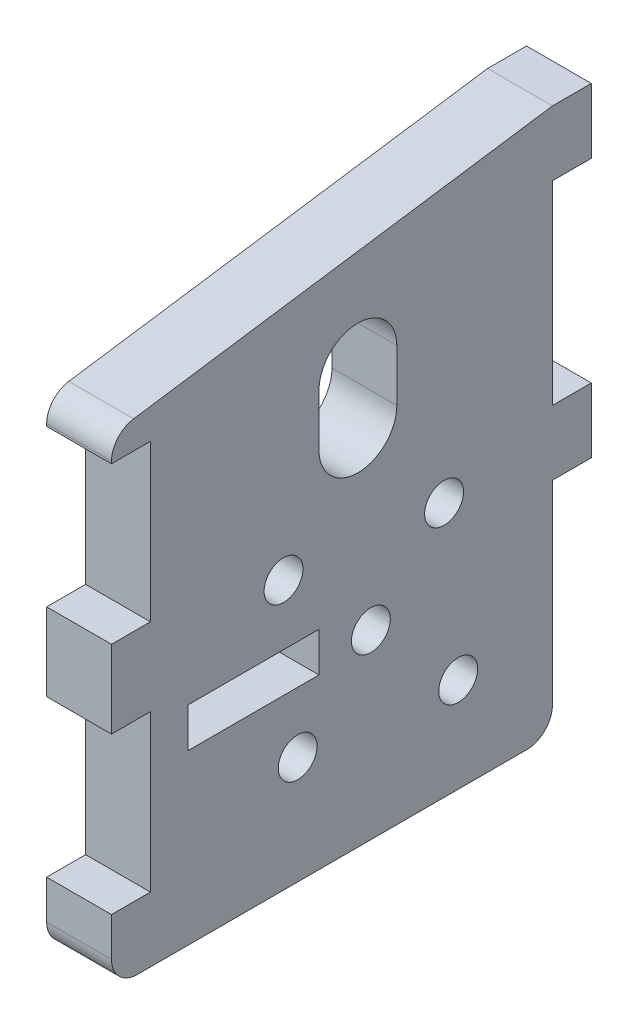
SolidWorks part; units mm, degrees
ref_plane "Front Plane" through (0, 0, 0) normal (0, 0, 1) x (1, 0, 0)
ref_plane "Top Plane" through (0, 0, 0) normal (0, 1, 0) x (1, 0, 0)
ref_plane "Right Plane" through (0, 0, 0) normal (1, 0, 0) x (0, 0, -1)
sketch "Sketch1" plane through (0, 0, 0) normal (1, 0, 0) x (0, 0, -1)
  line L0 (17, 28) -> (17, 23)
  line L1 (17, 28) -> (14, 28)
  line L2 (14, 28) -> (-20, 23)
  line L3 (-20, 23) -> (-20, -14)
  line L4 (14, -14) -> (-20, -14)
  line L6 (17, 23) -> (14, 23)
  line L7 (14, 23) -> (14, 8)
  line L8 (14, 8) -> (17, 8)
  line L9 (17, 8) -> (17, 3)
  line L10 (17, 3) -> (14, 3)
  line L11 (-6.7339, 6.7011) -> (6.7339, -6.7011) construction
  line L12 (20, 36.7745) -> (20, -39.1651) construction
  line L13 (5.643, 5.6706) -> (-5.643, -5.6706) construction
  line L14 (14, 3) -> (14, -14)
  circle A0 centre (0, 0) radius 18 construction
  circle A1 centre (-6.7339, 6.7011) radius 1.5
  circle A2 centre (-5.643, -5.6706) radius 1.5
  circle A3 centre (6.7339, -6.7011) radius 1.5
  circle A4 centre (5.643, 5.6706) radius 1.5
  circle A5 centre (0, 0) radius 1.5
  dimension "D2" = 36
  dimension "D4" = 3
  dimension "D1" = 20
  dimension "D3" = 13.4022
  dimension "D5" = 5
  dimension "D6" = 3
  dimension "D7" = 17
  dimension "D8" = 14
  dimension "D9" = 17
  dimension "D10" = 28
  dimension "D11" = 20
  dimension "D12" = 5
  dimension "D13" = 5.643
  dimension "D14" = 6.7339
extrude "Boss-Extrude1" add sketch "Sketch1" along normal blind 5
sketch "Sketch2" plane through (5, 0, 0) normal (1, 0, 0) x (0, 0, -1)
  line L0 (-20, 21.1) -> (-17, 21.1)
  line L1 (-14.1, 2.05) -> (-4, 2.05)
  line L2 (-14.1, 2.05) -> (-14.1, -1)
  line L3 (-14.1, -1) -> (-4, -1)
  line L4 (-4, 2.05) -> (-4, -1)
  line L5 (-20, -14) -> (14, -14) construction
  line L7 (-20, 23) -> (-20, -14) construction
  line L8 (-17, 21.1) -> (-17, 9.05)
  line L9 (-17, -9) -> (-20, -9)
  line L10 (-17, 9.05) -> (-20, 9.05)
  line L11 (-17, -9) -> (-17, 3.05)
  line L12 (-17, 3.05) -> (-20, 3.05)
  line L13 (-20, 21.1) -> (-20, 9.05)
  line L14 (-20, 3.05) -> (-20, -9)
  dimension "D3" = 10.1
  dimension "D1" = 3.05
  dimension "D2" = 13
  dimension "D4" = 4
  dimension "D5" = 3
  dimension "D6" = 12.05
  dimension "D7" = 12.05
  dimension "D8" = 6
  dimension "D9" = 5
extrude "Cut-Extrude1" cut sketch "Sketch2" against normal through all
sketch "Sketch4" plane through (5, 0, 0) normal (1, 0, 0) x (0, 0, -1)
  line L0 (-4, 18) -> (-4, 14)
  line L1 (2, 18) -> (2, 14)
  line L4 (14, 8) -> (14, 23) construction
  arc A0 (-4, 18) -> (2, 18) centre (-1, 18) cw
  arc A1 (-4, 14) -> (2, 14) centre (-1, 14) ccw
  dimension "D1" = 4
  dimension "D4" = 15
  dimension "D2" = 3
  dimension "D3" = 14
extrude "Cut-Extrude3" cut sketch "Sketch4" against normal blind 10
fillet "Fillet1" radius 2 3 edges at (2.5, 23, 20) (2.5, -14, 20) (2.5, -14, -14)
